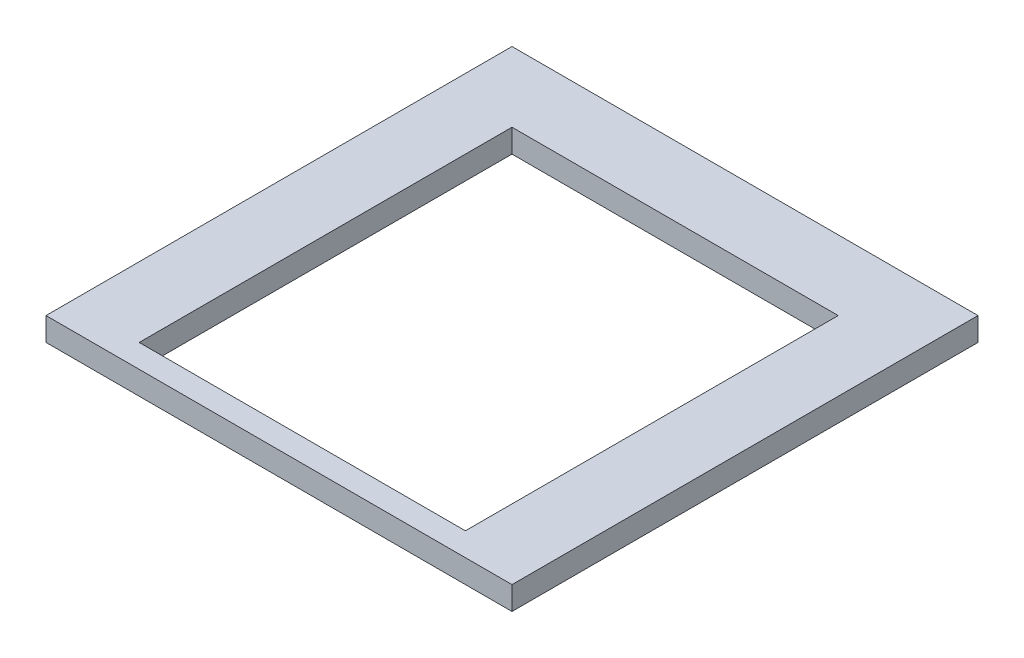
SolidWorks part; units mm, degrees
ref_plane "정면" through (0, 0, 0) normal (0, 0, 1) x (1, 0, 0)
ref_plane "윗면" through (0, 0, 0) normal (0, 1, 0) x (1, 0, 0)
ref_plane "우측면" through (0, 0, 0) normal (1, 0, 0) x (0, 0, -1)
sketch "스케치1" plane through (0, 0, 0) normal (0, 1, 0) x (1, 0, 0)
  line L1 (10, -10) -> (-10, -10)
  line L2 (10, -10) -> (10, 10)
  line L3 (10, 10) -> (-10, 10)
  line L4 (-10, -10) -> (-10, 10)
  line L5 (10, -10) -> (-10, 10) construction
  line L6 (10, 10) -> (-10, -10) construction
  point P0 (0, 0)
  dimension "D1" = 20
  dimension "D2" = 20
extrude "보스-돌출1" add sketch "스케치1" along normal blind 6
sketch "스케치3" plane through (0, 0, 0) normal (0, 1, 0) x (1, 0, 0)
  line L0 (-10, -10) -> (10, -10) construction
  line L1 (-9, 10) -> (9, 10)
  line L2 (-9, 10) -> (-9, -9)
  line L3 (-9, -9) -> (9, -9)
  line L4 (9, 10) -> (9, -9)
  line L5 (-10, 10) -> (-10, -10) construction
  dimension "D1" = 1
  dimension "D2" = 19
  dimension "D3" = 18
  dimension "D4" = 1
extrude "컷-돌출1" cut sketch "스케치3" along normal blind 6 from offset 1
sketch "스케치4" plane through (0, 0, 0) normal (0, 1, 0) x (1, 0, 0)
  line L1 (10, -10) -> (-10, -10)
  line L2 (10, -10) -> (10, 10)
  line L3 (10, 10) -> (-10, 10)
  line L4 (-10, -10) -> (-10, 10)
  line L5 (10, -10) -> (-10, 10) construction
  line L6 (10, 10) -> (-10, -10) construction
  point P0 (0, 0)
extrude "보스-돌출2" add sketch "스케치4" along normal blind 1 from offset 6 separate body
sketch "스케치7" plane through (0, 0, 0) normal (0, 1, 0) x (1, 0, 0)
  line L0 (-10, -10) -> (10, -10) construction
  line L1 (-7, 7) -> (7, 7)
  line L2 (-7, 7) -> (-7, -9)
  line L3 (-7, -9) -> (7, -9)
  line L4 (7, 7) -> (7, -9)
  line L5 (10, -10) -> (10, 10) construction
  dimension "D1" = 14
  dimension "D2" = 16
  dimension "D3" = 1
  dimension "D4" = 3
extrude "컷-돌출3" cut sketch "스케치7" against normal blind 1 from surface at 7 starting at face at (0, 7, 0)
sketch "스케치8" plane through (0, 7, 0) normal (0, 1, 0) x (1, 0, 0)
  line L4 (-10, 10) -> (-10, -10)
  line L5 (-10, -10) -> (10, -10)
  line L6 (10, -10) -> (10, 10)
  line L7 (10, 10) -> (-10, 10)
  line L8 (-10, 10) -> (-10, -10)
  line L9 (-10, -10) -> (10, -10)
  line L10 (10, -10) -> (10, 10)
  line L11 (10, 10) -> (-10, 10)
  dimension "D1" = 0
sketch "스케치9" plane through (0, 0, 0) normal (0, -1, 0) x (1, 0, 0)
  line L4 (-10, 10) -> (-10, -10)
  line L5 (-10, -10) -> (10, -10)
  line L6 (10, -10) -> (10, 10)
  line L7 (10, 10) -> (-10, 10)
  line L8 (-10, 10) -> (-10, -10)
  line L9 (-10, -10) -> (10, -10)
  line L10 (10, -10) -> (10, 10)
  line L11 (10, 10) -> (-10, 10)
  dimension "D1" = 0
extrude "컷-돌출5" cut sketch "스케치9" against normal blind 6
